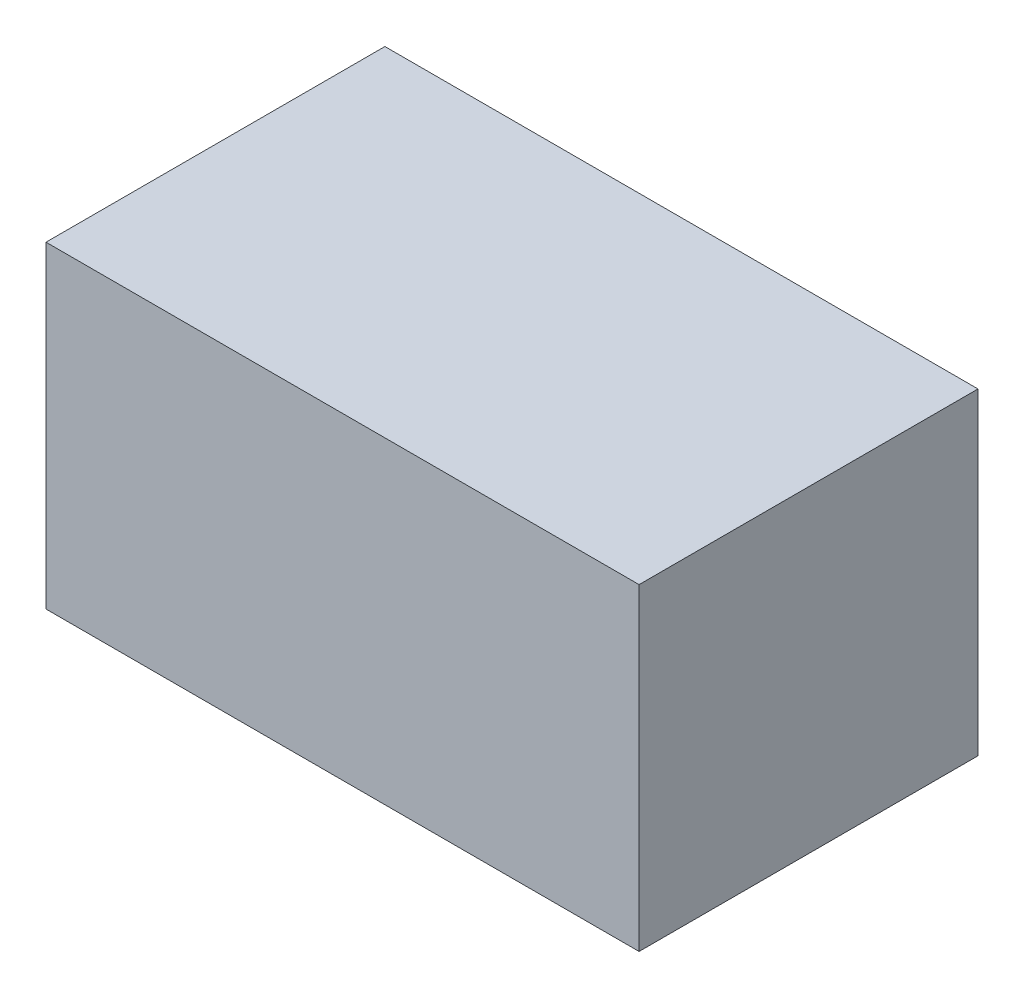
SolidWorks part; units mm, degrees
ref_plane "Płaszczyzna przednia" through (0, 0, 0) normal (0, 0, 1) x (1, 0, 0)
ref_plane "Płaszczyzna górna" through (0, 0, 0) normal (0, 1, 0) x (1, 0, 0)
ref_plane "Płaszczyzna prawa" through (0, 0, 0) normal (1, 0, 0) x (0, 0, -1)
sketch "Szkic1" plane through (0, 0, 0) normal (0, 1, 0) x (1, 0, 0)
  line L1 (-70, -40) -> (70, -40)
  line L2 (-70, -40) -> (-70, 40)
  line L3 (-70, 40) -> (70, 40)
  line L4 (70, -40) -> (70, 40)
  line L5 (-70, -40) -> (70, 40) construction
  line L6 (-70, 40) -> (70, -40) construction
  point P0 (0, 0)
  dimension "D1" = 80
  dimension "D2" = 140
extrude "Dodanie-wyciągnięcie1" add sketch "Szkic1" along normal blind 75
